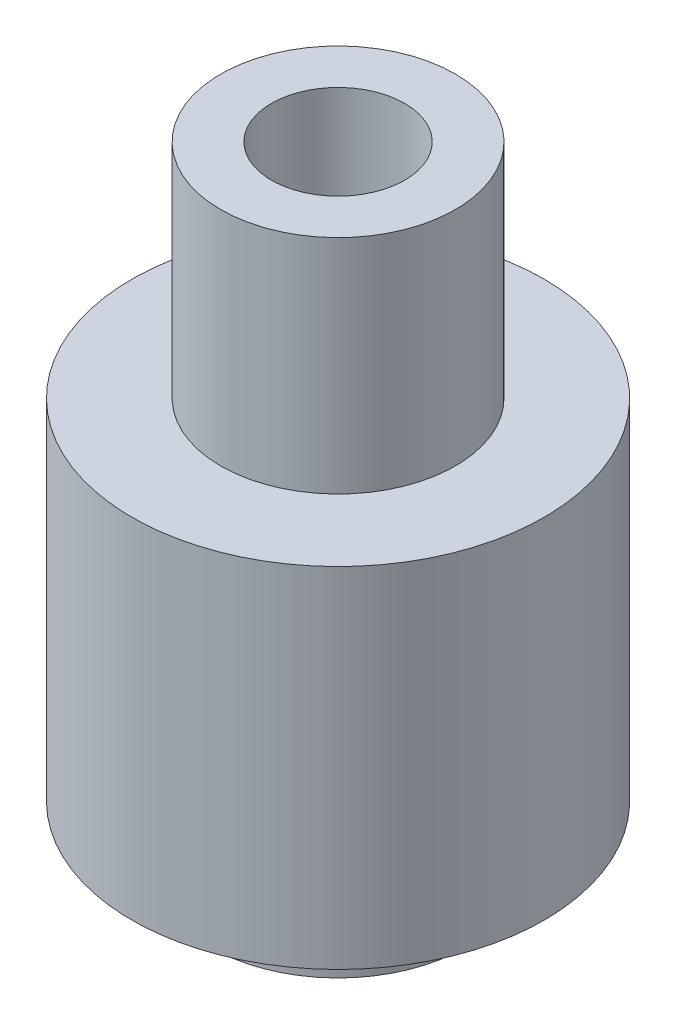
SolidWorks part; units mm, degrees
ref_plane "Front Plane" through (0, 0, 0) normal (0, 0, 1) x (1, 0, 0)
ref_plane "Top Plane" through (0, 0, 0) normal (0, 1, 0) x (1, 0, 0)
ref_plane "Right Plane" through (0, 0, 0) normal (1, 0, 0) x (0, 0, -1)
sketch "Reconstructed nominal axial profile" plane through (0, 0, 0) normal (0, 0, 1) x (1, 0, 0)
  line L0 (0, -500) -> (0, 50) construction
  line L1 (2.1, -13) -> (2.1, 7)
  line L2 (2.1, 7) -> (3.7, 7)
  line L3 (3.7, 7) -> (3.7, 0)
  line L4 (3.7, 0) -> (6.5, 0)
  line L5 (6.5, 0) -> (6.5, -11)
  line L6 (6.5, -11) -> (4, -11)
  line L7 (4, -11) -> (4, -13)
  line L8 (4, -13) -> (2.1, -13)
revolve "Native revolved geometry" add sketch "Reconstructed nominal axial profile" angle 360 about L0
